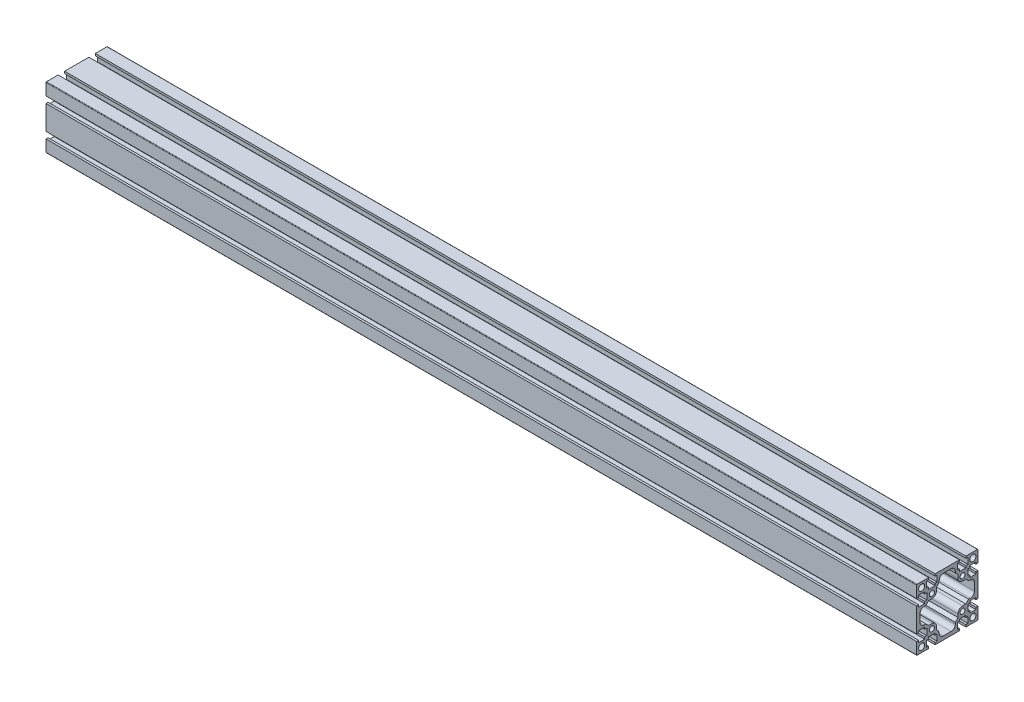
SolidWorks part; units mm, degrees
ref_plane "前视基准面" through (0, 0, 0) normal (0, 0, 1) x (1, 0, 0)
ref_plane "上视基准面" through (0, 0, 0) normal (0, 1, 0) x (1, 0, 0)
ref_plane "右视基准面" through (0, 0, 0) normal (1, 0, 0) x (0, 0, -1)
sketch "草图1" plane through (0, 0, 0) normal (0, 0, 1) x (1, 0, 0)
  line L0 (-425, 0) -> (425, 0)
  point P4 (0, 0)
  dimension "D1" = 850
other "铝型材（gb t5237-2004） 6060G(1)"
ref_plane "基准面1" through (-425, 0, 0) normal (1, 0, 0) x (0, 1, 0)
sketch "草图14" plane through (-425, 0, 0) normal (1, 0, 0) x (0, 1, 0)
  line L2 (28, -18.15) -> (30, -18.15)
  line L5 (22, -18.15) -> (20, -18.15)
  line L6 (20, -11.85) -> (20, -18.15)
  line L7 (22, -11.85) -> (20, -11.85)
  line L10 (28, -11.85) -> (30, -11.85)
  line L11 (28, 11.85) -> (30, 11.85)
  line L14 (22, 11.85) -> (20, 11.85)
  line L15 (20, 11.85) -> (20, 18.15)
  line L16 (22, 18.15) -> (20, 18.15)
  line L19 (28, 18.15) -> (30, 18.15)
  line L20 (11.85, 28) -> (11.85, 30)
  line L21 (11.85, 22) -> (11.85, 20)
  line L22 (11.85, 20) -> (18.15, 20)
  line L23 (18.15, 22) -> (18.15, 20)
  line L24 (18.15, 28) -> (18.15, 30)
  line L29 (18.15, -28) -> (18.15, -30)
  line L30 (18.15, -22) -> (18.15, -20)
  line L31 (11.85, -20) -> (18.15, -20)
  line L32 (11.85, -22) -> (11.85, -20)
  line L33 (11.85, -28) -> (11.85, -30)
  line L38 (-18.15, -28) -> (-18.15, -30)
  line L39 (-18.15, -28) -> (-20.15, -28)
  line L40 (-29.5, -30) -> (-18.15, -30)
  line L41 (-20.15, -22) -> (-20.15, -28)
  line L42 (-20.15, -22) -> (-18.15, -22)
  line L43 (-30, -29.5) -> (-30, -18.15)
  line L44 (-18.15, -22) -> (-18.15, -20)
  line L45 (-28, -18.15) -> (-30, -18.15)
  line L46 (-11.85, -20) -> (-18.15, -20)
  line L47 (-28, -18.15) -> (-28, -20.15)
  line L48 (-11.85, -22) -> (-11.85, -20)
  line L49 (-22, -20.15) -> (-28, -20.15)
  line L50 (-9.85, -22) -> (-11.85, -22)
  line L51 (-22, -20.15) -> (-22, -18.15)
  line L52 (-9.85, -22) -> (-9.85, -28)
  line L53 (-22, -18.15) -> (-20, -18.15)
  line L54 (-11.85, -28) -> (-9.85, -28)
  line L55 (-20, -11.85) -> (-20, -18.15)
  line L56 (-11.85, -28) -> (-11.85, -30)
  line L57 (-22, -11.85) -> (-20, -11.85)
  line L58 (-11.85, -30) -> (11.85, -30)
  line L59 (-22, -9.85) -> (-22, -11.85)
  line L61 (-22, -9.85) -> (-28, -9.85)
  line L62 (11.85, -28) -> (9.85, -28)
  line L63 (-28, -11.85) -> (-28, -9.85)
  line L64 (9.85, -22) -> (9.85, -28)
  line L65 (-28, -11.85) -> (-30, -11.85)
  line L66 (9.85, -22) -> (11.85, -22)
  line L67 (-30, 11.85) -> (-30, -11.85)
  line L69 (-28, 11.85) -> (-30, 11.85)
  line L71 (-28, 11.85) -> (-28, 9.85)
  line L73 (-22, 9.85) -> (-28, 9.85)
  line L74 (20.15, -22) -> (18.15, -22)
  line L75 (-22, 9.85) -> (-22, 11.85)
  line L76 (20.15, -22) -> (20.15, -28)
  line L77 (-22, 11.85) -> (-20, 11.85)
  line L78 (18.15, -28) -> (20.15, -28)
  line L79 (-20, 11.85) -> (-20, 18.15)
  line L81 (-22, 18.15) -> (-20, 18.15)
  line L82 (29.5, -30) -> (18.15, -30)
  line L83 (-22, 20.15) -> (-22, 18.15)
  line L84 (-22, 20.15) -> (-28, 20.15)
  line L85 (30, -18.15) -> (30, -29.5)
  line L86 (-28, 18.15) -> (-28, 20.15)
  line L88 (-28, 18.15) -> (-30, 18.15)
  line L89 (28, -18.15) -> (28, -20.15)
  line L90 (-30, 18.15) -> (-30, 29.5)
  line L91 (22, -20.15) -> (28, -20.15)
  line L92 (22, -20.15) -> (22, -18.15)
  line L93 (-29.5, 30) -> (-18.15, 30)
  line L95 (-18.15, 28) -> (-18.15, 30)
  line L97 (-18.15, 28) -> (-20.15, 28)
  line L99 (-20.15, 22) -> (-20.15, 28)
  line L100 (22, -9.85) -> (22, -11.85)
  line L101 (-20.15, 22) -> (-18.15, 22)
  line L102 (22, -9.85) -> (28, -9.85)
  line L103 (-18.15, 22) -> (-18.15, 20)
  line L104 (28, -11.85) -> (28, -9.85)
  line L105 (-11.85, 20) -> (-18.15, 20)
  line L107 (-11.85, 22) -> (-11.85, 20)
  line L108 (30, 11.85) -> (30, -11.85)
  line L109 (-9.85, 22) -> (-11.85, 22)
  line L111 (-9.85, 22) -> (-9.85, 28)
  line L112 (28, 11.85) -> (28, 9.85)
  line L113 (-11.85, 28) -> (-9.85, 28)
  line L114 (22, 9.85) -> (28, 9.85)
  line L115 (-11.85, 28) -> (-11.85, 30)
  line L116 (22, 9.85) -> (22, 11.85)
  line L117 (-11.85, 30) -> (11.85, 30)
  line L121 (11.85, 28) -> (9.85, 28)
  line L123 (9.85, 22) -> (9.85, 28)
  line L124 (22, 20.15) -> (22, 18.15)
  line L125 (9.85, 22) -> (11.85, 22)
  line L126 (22, 20.15) -> (28, 20.15)
  line L128 (28, 18.15) -> (28, 20.15)
  line L132 (30, 29.5) -> (30, 18.15)
  line L133 (20.15, 22) -> (18.15, 22)
  line L134 (20.15, 22) -> (20.15, 28)
  line L135 (29.5, 30) -> (18.15, 30)
  line L136 (18.15, 28) -> (20.15, 28)
  line L144 (18.15, -10.5) -> (20.8, -7.85)
  line L145 (22.5, -7.85) -> (20.8, -7.85)
  line L146 (15, -10.5) -> (18.15, -10.5)
  line L147 (26.5, -3.85) -> (26.5, 3.85)
  line L148 (10.5, -18.15) -> (10.5, -15)
  line L149 (7.85, -20.8) -> (10.5, -18.15)
  line L150 (22.5, 7.85) -> (20.8, 7.85)
  line L151 (7.85, -22.5) -> (7.85, -20.8)
  line L152 (18.15, 10.5) -> (20.8, 7.85)
  line L153 (18.15, 10.5) -> (15, 10.5)
  line L154 (-3.85, -26.5) -> (3.85, -26.5)
  line L155 (10.5, 15) -> (10.5, 18.15)
  line L156 (-7.85, -20.8) -> (-7.85, -22.5)
  line L157 (10.5, 18.15) -> (7.85, 20.8)
  line L158 (-10.5, -18.15) -> (-7.85, -20.8)
  line L159 (7.85, 20.8) -> (7.85, 22.5)
  line L160 (-10.5, -15) -> (-10.5, -18.15)
  line L161 (3.85, 26.5) -> (-3.85, 26.5)
  line L162 (-18.15, -10.5) -> (-15, -10.5)
  line L163 (-20.8, -7.85) -> (-18.15, -10.5)
  line L164 (-7.85, 22.5) -> (-7.85, 20.8)
  line L165 (-22.5, -7.85) -> (-20.8, -7.85)
  line L166 (-7.85, 20.8) -> (-10.5, 18.15)
  line L167 (-10.5, 18.15) -> (-10.5, 15)
  line L168 (-26.5, 3.85) -> (-26.5, -3.85)
  line L169 (-15, 10.5) -> (-18.15, 10.5)
  line L170 (-20.8, 7.85) -> (-22.5, 7.85)
  line L171 (-18.15, 10.5) -> (-20.8, 7.85)
  arc A0 (-30, -29.5) -> (-29.5, -30) centre (-29.5, -29.5) ccw
  arc A1 (29.5, -30) -> (30, -29.5) centre (29.5, -29.5) ccw
  arc A2 (-29.5, 30) -> (-30, 29.5) centre (-29.5, 29.5) ccw
  arc A3 (30, 29.5) -> (29.5, 30) centre (29.5, 29.5) ccw
  circle A4 centre (25, 25) radius 3
  circle A5 centre (-15, 15) radius 2.5
  circle A6 centre (-25, -25) radius 3
  circle A7 centre (25, -25) radius 3
  circle A8 centre (15, -15) radius 2.5
  circle A9 centre (-15, -15) radius 2.5
  circle A10 centre (-25, 25) radius 3
  circle A11 centre (15, 15) radius 2.5
  arc A12 (22.5, -7.85) -> (26.5, -3.85) centre (22.5, -3.85) ccw
  arc A13 (15, -10.5) -> (10.5, -15) centre (15, -15) ccw
  arc A14 (26.5, 3.85) -> (22.5, 7.85) centre (22.5, 3.85) ccw
  arc A15 (3.85, -26.5) -> (7.85, -22.5) centre (3.85, -22.5) ccw
  arc A16 (10.5, 15) -> (15, 10.5) centre (15, 15) ccw
  arc A17 (-7.85, -22.5) -> (-3.85, -26.5) centre (-3.85, -22.5) ccw
  arc A18 (7.85, 22.5) -> (3.85, 26.5) centre (3.85, 22.5) ccw
  arc A19 (-10.5, -15) -> (-15, -10.5) centre (-15, -15) ccw
  arc A20 (-3.85, 26.5) -> (-7.85, 22.5) centre (-3.85, 22.5) ccw
  arc A21 (-26.5, -3.85) -> (-22.5, -7.85) centre (-22.5, -3.85) ccw
  arc A22 (-15, 10.5) -> (-10.5, 15) centre (-15, 15) ccw
  arc A23 (-22.5, 7.85) -> (-26.5, 3.85) centre (-22.5, 3.85) ccw
  point P0 (0, 0)
